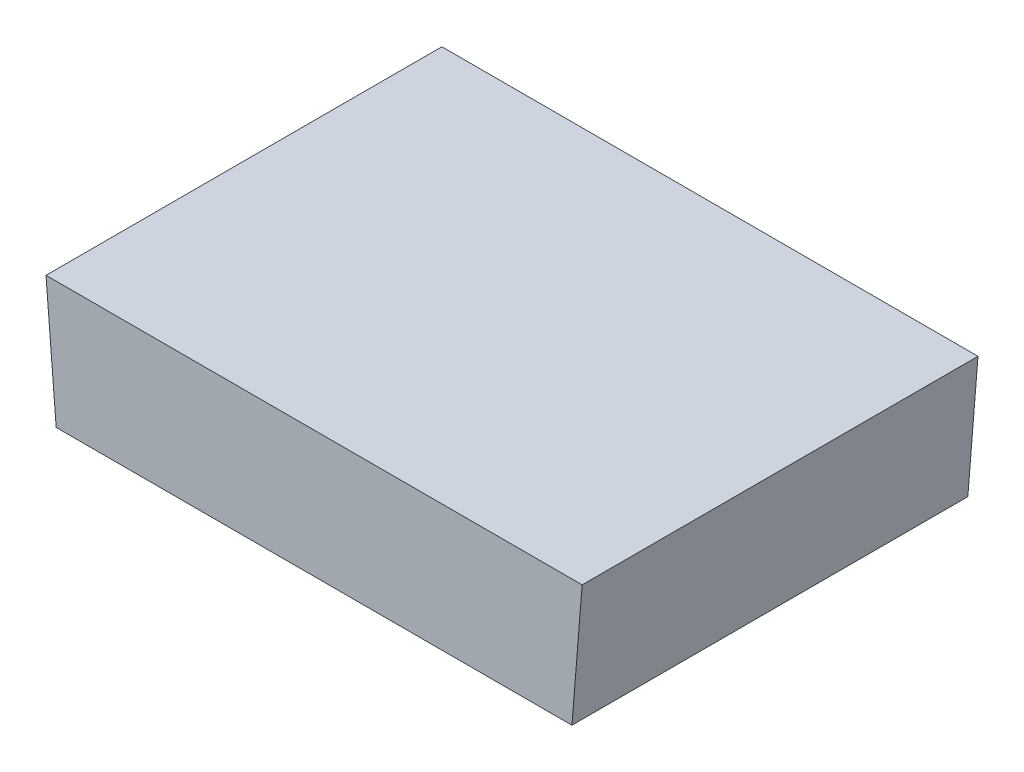
SolidWorks part; units mm, degrees
ref_plane "Front Plane" through (0, 0, 0) normal (0, 0, 1) x (1, 0, 0)
ref_plane "Top Plane" through (0, 0, 0) normal (0, 1, 0) x (1, 0, 0)
ref_plane "Right Plane" through (0, 0, 0) normal (1, 0, 0) x (0, 0, -1)
sketch "Sketch2" plane through (0, 0, 0) normal (0, 0, 1) x (1, 0, 0)
  line L0 (0, 10.236) -> (0, -11.989) construction
  line L1 (45.2437, -11.989) -> (-45.2437, -11.989)
  line L2 (47.0297, 10.236) -> (-47.0297, 10.236)
  line L3 (-47.0297, 10.236) -> (-45.2437, -11.989)
  line L4 (45.2437, -11.989) -> (47.0297, 10.236)
  point P6 (0, -11.989)
  point P9 (0, 10.236)
  dimension "D1" = 22.225
  dimension "D2" = 94.0594
  dimension "D3" = 90.4875
extrude "Boss-Extrude1" add sketch "Sketch2" along normal blind 69.4531 contours L2 L3 L1 L4
sketch "Sketch3" plane through (0, -11.989, 0) normal (0, -1, 0) x (1, 0, 0)
  line L0 (29.1525, 33.4206) -> (29.1525, 38.7784) construction
  line L1 (23.8939, 33.4206) -> (23.8939, 38.7784)
  line L2 (34.4111, 33.4206) -> (34.4111, 38.7784)
  line L3 (-27.922, 32.4533) -> (-27.922, 37.8111) construction
  line L4 (-33.1806, 32.4533) -> (-33.1806, 37.8111)
  line L5 (-22.6634, 32.4533) -> (-22.6634, 37.8111)
  line L6 (45.2437, 0) -> (-45.2438, 0) construction
  line L7 (-45.2438, 69.4531) -> (-45.2438, 0) construction
  line L9 (45.2437, 1.778) -> (-45.2438, 1.778) construction
  line L10 (45.2437, 69.4531) -> (45.2437, 0) construction
  line L11 (45.2437, 67.6751) -> (-45.2438, 67.6751) construction
  line L12 (45.2437, 69.4531) -> (-45.2438, 69.4531) construction
  circle A0 centre (36.0164, 10.4259) radius 6.0523
  circle A1 centre (-36.0164, 9.2273) radius 6.0523
  circle A2 centre (-36.0164, 57.2492) radius 6.0523
  circle A3 centre (36.0164, 58.4478) radius 6.0523
  arc A4 (23.8939, 33.4206) -> (34.4111, 33.4206) centre (29.1525, 33.4206) ccw
  arc A5 (34.4111, 38.7784) -> (23.8939, 38.7784) centre (29.1525, 38.7784) ccw
  arc A6 (-33.1806, 32.4533) -> (-22.6634, 32.4533) centre (-27.922, 32.4533) ccw
  arc A7 (-22.6634, 37.8111) -> (-33.1806, 37.8111) centre (-27.922, 37.8111) ccw
  point P10 (29.1525, 36.0995)
  point P15 (-27.922, 35.1322)
  point P22 (-27.922, 43.0697)
  point P23 (-27.922, 27.1947)
  point P24 (29.1525, 44.037)
  point P25 (29.1525, 28.162)
  dimension "D1" = 12.1047
  dimension "D2" = 12.1047
  dimension "D3" = 12.1047
  dimension "D4" = 12.1047
  dimension "D5" = 72.0328
  dimension "D6" = 72.0328
  dimension "D7" = 15.875
  dimension "D11" = 48.0219
  dimension "D12" = 48.0219
  dimension "D13" = 1.778
  dimension "D14" = 9.2273
  dimension "D16" = 1.778
  dimension "D17" = 9.2273
  dimension "D8" = 15.875
  dimension "D9" = 10.5172
  dimension "D10" = 10.5172
extrude "Boss-Extrude2" add sketch "Sketch3" along normal blind 3.175
